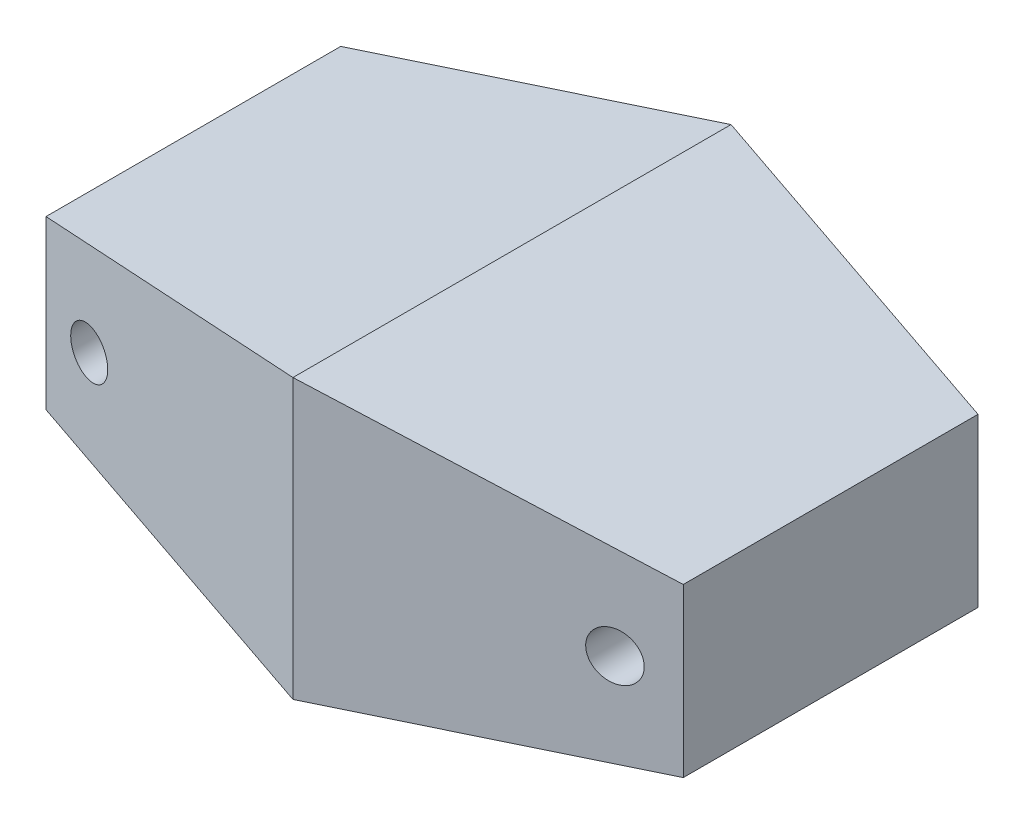
SolidWorks part; units mm, degrees
ref_plane "Front Plane" through (0, 0, 0) normal (0, 0, 1) x (1, 0, 0)
ref_plane "Top Plane" through (0, 0, 0) normal (0, 1, 0) x (1, 0, 0)
ref_plane "Right Plane" through (0, 0, 0) normal (1, 0, 0) x (0, 0, -1)
sketch "Sketch1" plane through (0, 0, 0) normal (0, 0, 1) x (1, 0, 0)
  line L1 (-40, -17.5) -> (40, -17.5)
  line L2 (-40, -17.5) -> (-40, 17.5)
  line L3 (-40, 17.5) -> (40, 17.5)
  line L4 (40, -17.5) -> (40, 17.5)
  line L5 (-40, -17.5) -> (40, 17.5) construction
  line L6 (-40, 17.5) -> (40, -17.5) construction
  point P0 (0, 0)
  dimension "D1" = 80
  dimension "D2" = 35
extrude "Boss-Extrude1" add sketch "Sketch1" along normal blind 55
sketch "Sketch2" plane through (0, 17.5, 0) normal (0, 1, 0) x (1, 0, 0)
  line L0 (0, 0) -> (0, -55) construction
  line L1 (40, -55) -> (-40, -55) construction
  line L2 (-40, -27.5) -> (40, -27.5) construction
  line L3 (-40, -55) -> (-40, 0) construction
  line L4 (40, -55) -> (40, 0) construction
  line L5 (0, -55) -> (-40, -46)
  line L6 (0, -55) -> (40, -46)
  line L7 (0, 0) -> (40, -9)
  line L8 (0, 0) -> (-40, -9)
  line L9 (-40, -46) -> (-40, -55)
  line L10 (-40, -55) -> (0, -55)
  line L11 (0, -55) -> (40, -55)
  line L12 (40, -55) -> (40, -46)
  line L13 (40, -9) -> (40, 0)
  line L14 (40, 0) -> (0, 0)
  line L15 (-40, -9) -> (-40, 0)
  line L16 (-40, 0) -> (0, 0)
  line M8 (40, 0) -> (-40, 0)
  line M9 (-40, 0) -> (-40, -55)
  line M10 (-40, -55) -> (40, -55)
  line M11 (40, -55) -> (40, 0)
  dimension "D1" = 9
extrude "Cut-Extrude1" cut sketch "Sketch2" against normal blind 55 contours L5 M10 M9 | L6 M10 M11 | L7 M8 M11 | L8 M8 M9
sketch "Sketch5" plane through (0, 0, 0) normal (0, 0, 1) x (1, 0, 0)
  line L0 (0, 17.5) -> (-40, 10.5)
  line L1 (-40, -17.5) -> (-40, 17.5) construction
  line L2 (-40, 0) -> (40, 0) construction
  line L3 (40, -17.5) -> (40, 17.5) construction
  line L4 (0, 17.5) -> (0, -17.5) construction
  line L5 (0, 17.5) -> (40, 10.5)
  line L6 (0, -17.5) -> (40, -10.5)
  line L7 (0, -17.5) -> (-40, -10.5)
  line L8 (-40, 10.5) -> (-40, 17.5)
  line L9 (-40, 17.5) -> (0, 17.5)
  line L10 (0, 17.5) -> (40, 17.5)
  line L11 (40, 17.5) -> (40, 10.5)
  line L12 (40, -10.5) -> (40, -17.5)
  line L13 (0, -17.5) -> (40, -17.5) construction
  line L14 (40, -17.5) -> (0, -17.5)
  line L15 (-40, -10.5) -> (-40, -17.5)
  line L16 (-40, -17.5) -> (0, -17.5)
  dimension "D1" = 7
extrude "Cut-Extrude2" cut sketch "Sketch5" along normal through all both and the other way through all contours L11 L10 L5 | L9 L8 L0 | L14 L12 L6 | L15 L16 L7
sketch "Sketch6" plane through (0, 0, 0) normal (0, 0, 1) x (1, 0, 0)
  line L0 (-40, -10.5) -> (-40, 10.5) construction
  line L1 (0, 0) -> (0, 4.0272) construction
  line L2 (0, 17.5) -> (0, -17.5) construction
  circle A0 centre (-33, 0) radius 3
  circle A1 centre (33, 0) radius 3
  dimension "D1" = 7
extrude "Cut-Extrude3" cut sketch "Sketch6" against normal through all both and the other way through all
